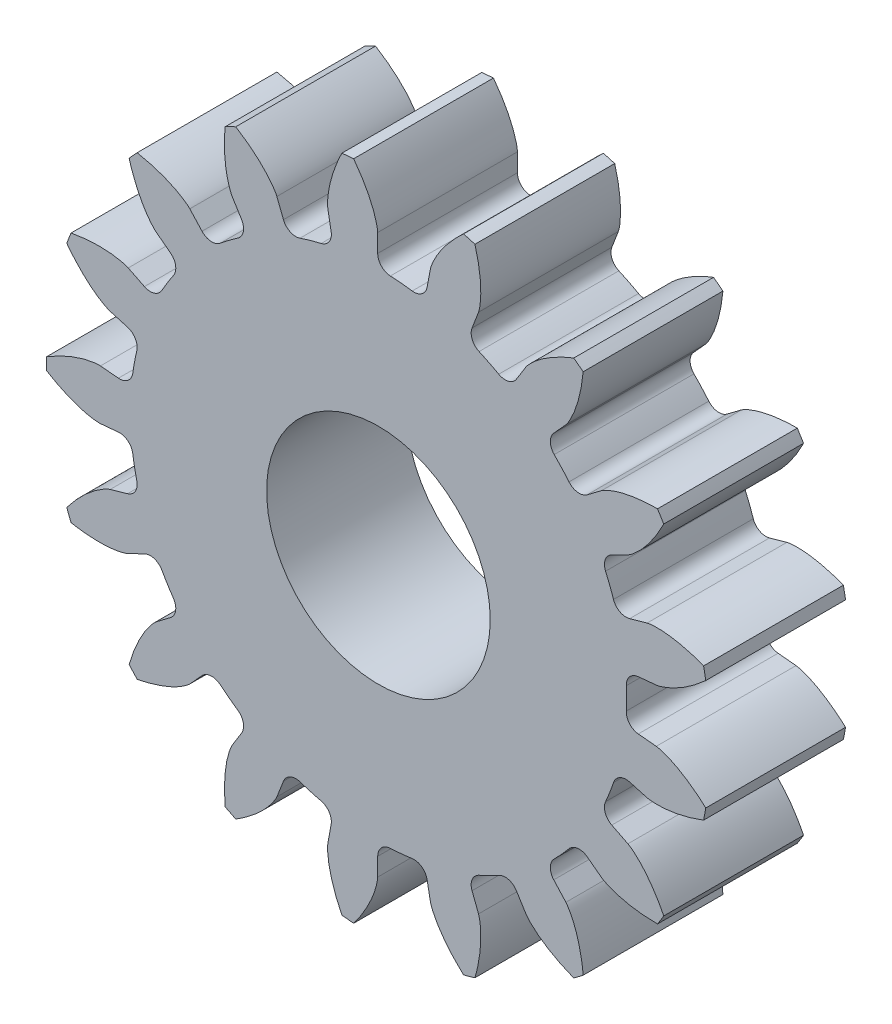
SolidWorks part; units mm, degrees
ref_plane "Front Plane" through (0, 0, 0) normal (0, 0, 1) x (1, 0, 0)
ref_plane "Top Plane" through (0, 0, 0) normal (0, 1, 0) x (1, 0, 0)
ref_plane "Right Plane" through (0, 0, 0) normal (1, 0, 0) x (0, 0, -1)
ref_axis "Gear Axis" through (0, 0, -0.2501) along (0, 0, 1)
sketch "Blank Sketch" plane through (0, 0, 0) normal (0, 0, 1) x (1, 0, 0)
  circle A0 centre (0, 0) radius 11.875
  dimension "OD" = 23.75
extrude "Blank" add sketch "Blank Sketch" along normal blind 5
sketch "Tooth Space Sketch" plane through (0, 0, 0) normal (0, 0, 1) x (1, 0, 0)
  line L0 (9.9391, 0.9485) -> (9.2957, 0.8871)
  line L1 (9.9391, -0.9485) -> (9.2957, -0.8871)
  line L2 (12.7424, 3.1457) -> (12.7424, -3.1457)
  arc A0 (9.2957, 0.8871) -> (8.8663, 0.3932) centre (9.3408, 0.4142) ccw
  arc A1 (8.8663, -0.3932) -> (9.2957, -0.8871) centre (9.3408, -0.4142) ccw
  arc A2 (8.8663, -0.3932) -> (8.8663, 0.3932) centre (0, 0) ccw
  spline S0 degree 4 poles (9.9391, 0.9485) (9.9444, 0.9491) (9.9594, 0.9511) (9.9875, 0.9561) (10.033, 0.9658) (10.0906, 0.9807) (10.1644, 1.0027) (10.2505, 1.0321) (10.344, 1.0681) (10.4445, 1.1112) (10.5435, 1.1577) (10.6412, 1.2072) (10.7373, 1.2593) (10.8523, 1.3258) (10.9883, 1.4101) (11.1441, 1.5151) (11.3169, 1.6419) (11.4885, 1.7791) (11.6537, 1.9206) (11.816, 2.0708) (11.9698, 2.2212) (12.1246, 2.3846) (12.2649, 2.5391) (12.4162, 2.7198) (12.5367, 2.8679) (12.6891, 3.071) (12.7772, 3.1933) (12.878, 3.3391) (12.9216, 3.4052) (12.9484, 3.4459) knots 0 0 0 0 0 0.005377 0.015084 0.028532 0.04661 0.064855 0.092111 0.119476 0.146842 0.174209 0.201575 0.228941 0.256307 0.307035 0.361767 0.4165 0.471232 0.525964 0.580697 0.635429 0.690161 0.744894 0.799626 0.854358 0.909091 0.954545 1 1 1 1 1 construction
  spline S1 degree 4 poles (9.9391, 0.9485) (9.9444, 0.9491) (9.9594, 0.9511) (9.9875, 0.9561) (10.033, 0.9658) (10.0906, 0.9807) (10.1644, 1.0027) (10.2505, 1.0321) (10.344, 1.0681) (10.4445, 1.1112) (10.5435, 1.1577) (10.6412, 1.2072) (10.7373, 1.2593) (10.8523, 1.3258) (10.9883, 1.4101) (11.1441, 1.5151) (11.3169, 1.6419) (11.4885, 1.7791) (11.6537, 1.9206) (11.816, 2.0708) (11.9698, 2.2212) (12.1246, 2.3846) (12.2649, 2.5391) (12.4162, 2.7198) (12.5367, 2.8679) (12.6561, 3.027) (12.7135, 3.1053) (12.7424, 3.1457) knots 0 0 0 0 0 0.005377 0.015084 0.028532 0.04661 0.064855 0.092111 0.119476 0.146842 0.174209 0.201575 0.228941 0.256307 0.307035 0.361767 0.4165 0.471232 0.525964 0.580697 0.635429 0.690161 0.744894 0.799626 0.854358 0.909091 0.909091 0.909091 0.909091 0.909091
  spline S2 degree 4 poles (9.9391, -0.9485) (9.9444, -0.9491) (9.9594, -0.9511) (9.9875, -0.9561) (10.033, -0.9658) (10.0906, -0.9807) (10.1644, -1.0027) (10.2505, -1.0321) (10.344, -1.0681) (10.4445, -1.1112) (10.5435, -1.1577) (10.6412, -1.2072) (10.7373, -1.2593) (10.8523, -1.3258) (10.9883, -1.4101) (11.1441, -1.5151) (11.3169, -1.6419) (11.4885, -1.7791) (11.6537, -1.9206) (11.816, -2.0708) (11.9698, -2.2212) (12.1246, -2.3846) (12.2649, -2.5391) (12.4162, -2.7198) (12.5367, -2.8679) (12.6891, -3.071) (12.7772, -3.1933) (12.878, -3.3391) (12.9216, -3.4052) (12.9484, -3.4459) knots 0 0 0 0 0 0.005377 0.015084 0.028532 0.04661 0.064855 0.092111 0.119476 0.146842 0.174209 0.201575 0.228941 0.256307 0.307035 0.361767 0.4165 0.471232 0.525964 0.580697 0.635429 0.690161 0.744894 0.799626 0.854358 0.909091 0.954545 1 1 1 1 1 construction
  spline S3 degree 4 poles (9.9391, -0.9485) (9.9444, -0.9491) (9.9594, -0.9511) (9.9875, -0.9561) (10.033, -0.9658) (10.0906, -0.9807) (10.1644, -1.0027) (10.2505, -1.0321) (10.344, -1.0681) (10.4445, -1.1112) (10.5435, -1.1577) (10.6412, -1.2072) (10.7373, -1.2593) (10.8523, -1.3258) (10.9883, -1.4101) (11.1441, -1.5151) (11.3169, -1.6419) (11.4885, -1.7791) (11.6537, -1.9206) (11.816, -2.0708) (11.9698, -2.2212) (12.1246, -2.3846) (12.2649, -2.5391) (12.4162, -2.7198) (12.5367, -2.8679) (12.6561, -3.027) (12.7135, -3.1053) (12.7424, -3.1457) knots 0 0 0 0 0 0.005377 0.015084 0.028532 0.04661 0.064855 0.092111 0.119476 0.146842 0.174209 0.201575 0.228941 0.256307 0.307035 0.361767 0.4165 0.471232 0.525964 0.580697 0.635429 0.690161 0.744894 0.799626 0.854358 0.909091 0.909091 0.909091 0.909091 0.909091
  dimension "Root" = 8.875
  dimension "Fillet" = 0.475
extrude "Tooth Space" cut sketch "Tooth Space Sketch" against normal through all both and the other way through all both
pattern_circular "Teeth" count 17 over 360 about axis through (0, 0, -0.2501) along (0, 0, 1) of "Tooth Space"
sketch "Bore Sketch" plane through (0, 0, 0) normal (0, 0, 1) x (1, 0, 0)
  circle A0 centre (0, 0) radius 4
  dimension "Bore" = 8
extrude "Bore" cut sketch "Bore Sketch" against normal through all both and the other way through all both
equation "\"No. of Teeth\"= 17"
equation "\"Module\"= 1.25"
equation "\"Bore Diameter\"= 8"
equation "\"Pressure Angle\"= 20"
equation "\"Outer Diameter\"= ( \"No. of Teeth\" + 2 ) * \"Module\""
equation "\"Pitch Diameter\"= \"No. of Teeth\" * \"Module\""
equation "\"Backlash\"= 0.3 * \"Module\""
equation "\"Arc Length\"= ( ( \"Module\" * pi ) / 2 + \"Backlash\" )"
equation "\"Fillet Radius\"= 0.38 * \"Module\""
equation "\"Tooth Depth\"= IIF ( \"Module\" <= 1.25 , \"Module\" * 2.4 , \"Module\" * 2.25 )"
equation "\"Face Width\"= 5"
equation "\"Root Diameter\"= \"Outer Diameter\" - 2 * \"Tooth Depth\""
equation "\"Base Diameter\"= \"Pitch Diameter\" * cos ( \"Pressure Angle\" )"
equation "\"Base Radius\"= \"Base Diameter\" / 2"
equation "\"Tooth Thickness\"= \"Module\" * pi - \"Arc Length\""
equation "\"Half Space Angle\"= ( \"Arc Length\" / \"Pitch Diameter\" ) * 180 / pi"
equation "\"Involute Fn\"= tan ( \"Pressure Angle\" ) - \"Pressure Angle\" * pi / 180"
equation "\"Flank Offset\"= \"Arc Length\" / \"Pitch Diameter\" - \"Involute Fn\""
equation "\"Tip Cap Diameter\"= \"Outer Diameter\" + 2 * \"Module\""
equation "\"Flank Start Diameter\"= IIF ( \"Base Diameter\" >= ( \"Root Diameter\" + 3 * \"Fillet Radius\" ) , \"Base Diameter\" , \"Root Diameter\" + 3 * \"Fillet Radius\" )"
equation "\"Involute t1\"= ( abs ( ( \"Flank Start Diameter\" / \"Base Diameter\" ) ^ 2 - 1 ) ) ^ 0.5"
equation "\"Involute t2\"= ( abs ( ( \"Tip Cap Diameter\" / \"Base Diameter\" ) ^ 2 - 1 ) ) ^ 0.5"
equation "\"Flank Arc Radius\"= ( \"Pitch Diameter\" / 2 ) * sin ( \"Pressure Angle\" )"
equation "\"Flank Centre Angle\"= \"Half Space Angle\" + \"Pressure Angle\""
equation "\"OD@Blank Sketch\"= \"Outer Diameter\""
equation "\"Width@Blank\"= \"Face Width\""
equation "\"Root@Tooth Space Sketch\"= \"Root Diameter\" / 2"
equation "\"Fillet@Tooth Space Sketch\"= \"Fillet Radius\""
equation "\"Count@Teeth\"= \"No. of Teeth\""
equation "\"Bore@Bore Sketch\"= \"Bore Diameter\""
